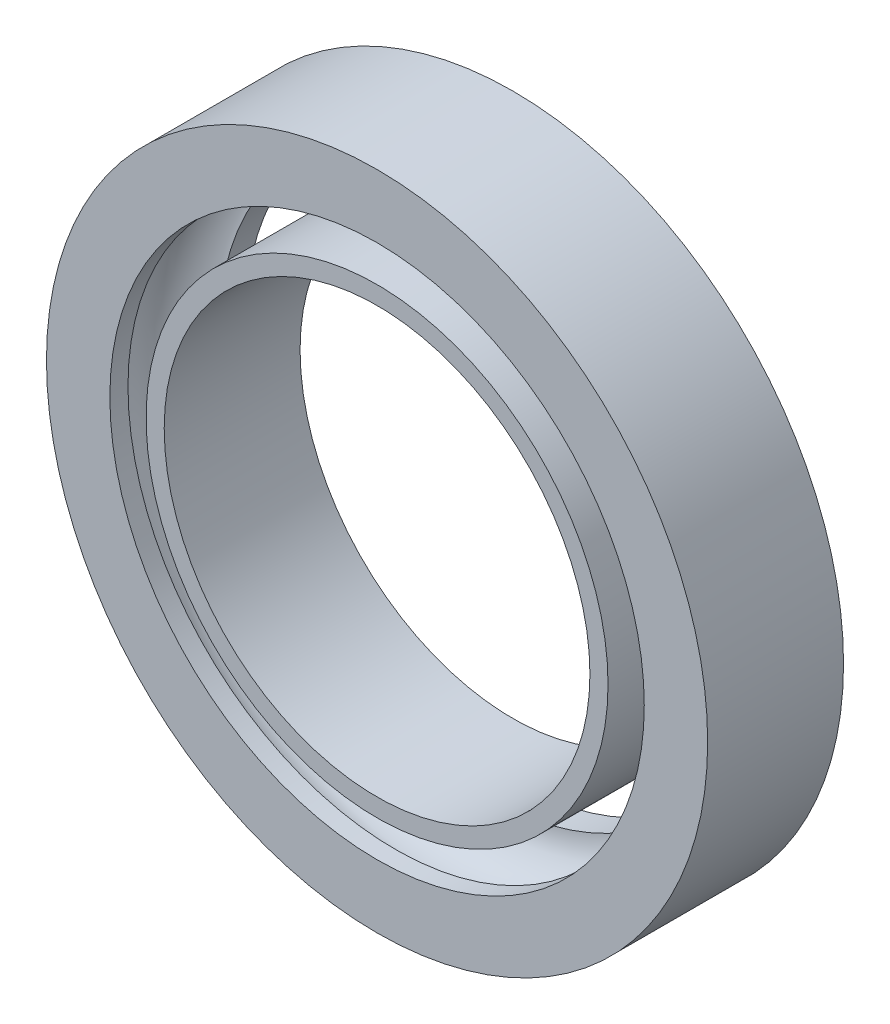
SolidWorks part; units mm, degrees
ref_plane "前视基准面" through (0, 0, 0) normal (0, 0, 1) x (1, 0, 0)
ref_plane "上视基准面" through (0, 0, 0) normal (0, 1, 0) x (1, 0, 0)
ref_plane "右视基准面" through (0, 0, 0) normal (1, 0, 0) x (0, 0, -1)
sketch "草图1" plane through (0, 0, 0) normal (0, 0, 1) x (1, 0, 0)
  circle A0 centre (0, 0) radius 23.5
  circle A1 centre (0, 0) radius 25.5
  dimension "D1" = 47
  dimension "D2" = 2
extrude "凸台-拉伸2" add sketch "草图1" along normal blind 15
sketch "草图3" plane through (0, 0, 0) normal (0, 0, 1) x (1, 0, 0)
  circle A0 centre (0, 0) radius 29.5
  circle A1 centre (0, 0) radius 36.5
  dimension "D1" = 59
  dimension "D2" = 7
extrude "凸台-拉伸3" add sketch "草图3" along normal blind 15 separate body
sketch "草图5" plane through (0, 0, 0) normal (0, 1, 0) x (1, 0, 0)
  line L0 (-29.5, 0) -> (-29.5, -15) construction
  line L1 (-29.5, -15) -> (29.5, -15) construction
  line L2 (-29.5, -3) -> (-29.5, -13)
  line L3 (0, 0) -> (0, -20.0684) construction
  arc A0 (-29.5, -3) -> (-29.5, -13) centre (-29.5, -8) ccw
  point P6 (-29.5, -3)
  dimension "D1" = 10
  dimension "D2" = 7
revolve "切除-旋转2" cut sketch "草图5" angle 360 about L3
